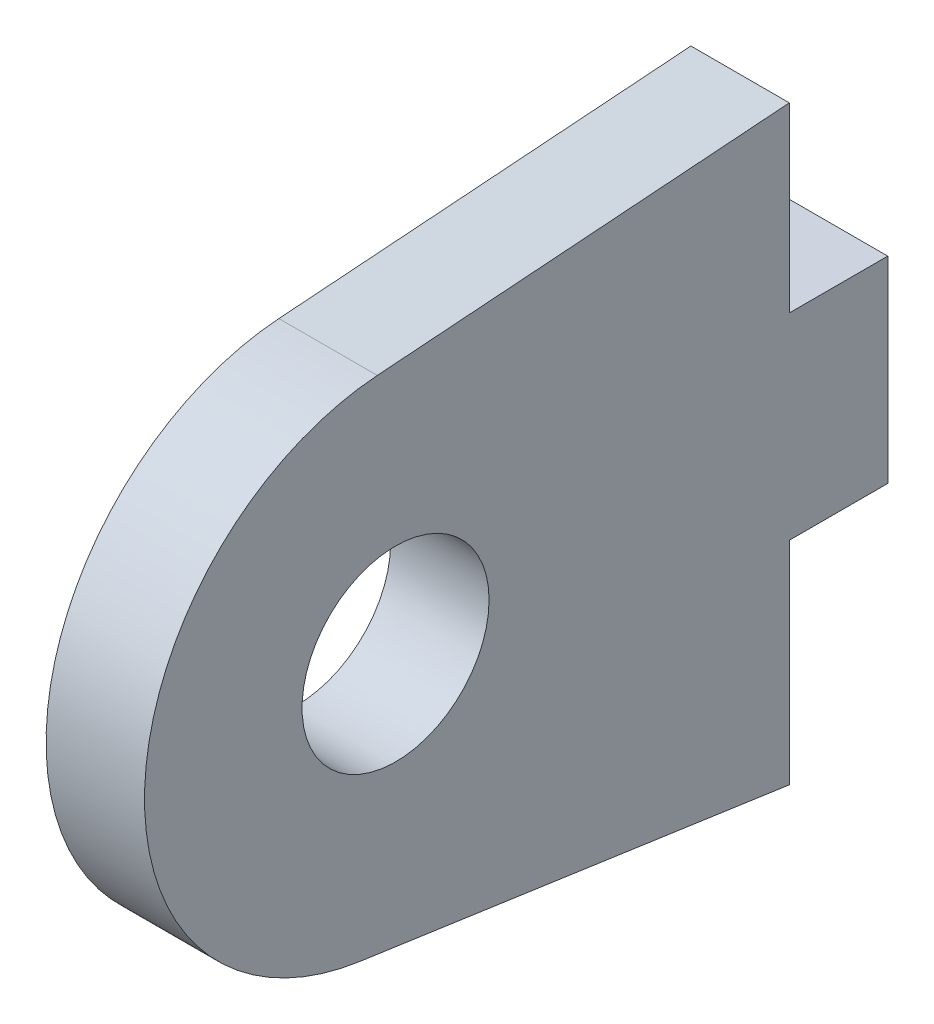
SolidWorks part; units mm, degrees
material "AISI 1020 Steel, Cold Rolled"
ref_plane "Front Plane" through (0, 0, 0) normal (1, 0, 0) x (0, 1, 0)
ref_plane "Top Plane" through (0, 0, 0) normal (0, 0, 1) x (0, 1, 0)
ref_plane "Right Plane" through (0, 0, 0) normal (0, 1, 0) x (-1, 0, 0)
sketch "Sketch1" plane through (0, 0, 0) normal (1, 0, 0) x (0, 1, 0)
  line L0 (-15.7577, 0) -> (-5, 0)
  line L1 (0, 0) -> (0, 20) construction
  line L2 (-15.7577, 0) -> (-12.6201, 21.8151)
  line L3 (14.2423, 0) -> (12.7162, 20.9273)
  line L4 (0, 0) -> (0, -5) construction
  line L5 (5, -5) -> (-5, -5)
  line L6 (-5, -5) -> (-5, 0)
  line L7 (5, -5) -> (5, 0)
  line L8 (5, 0) -> (14.2423, 0)
  line L9 (0, 0) -> (5, 0) construction
  line L10 (-5, 0) -> (0, 0) construction
  line L11 (0, 20) -> (0, 4.6155) construction
  circle A0 centre (0, 20) radius 4.75
  arc A1 (12.7162, 20.9273) -> (-12.6201, 21.8151) centre (0, 20) ccw
  arc A2 (0, 7.25) -> (12.7162, 20.9273) centre (0, 20) ccw construction
  circle A3 centre (0, 20) radius 12.75 construction
  point P4 (0, 0)
  point P11 (12, 20)
  point P17 (0, -5)
  dimension "D3" = 9.5
  dimension "D4" = 8
  dimension "D1" = 30
  dimension "D2" = 20
  dimension "D5" = 5
  dimension "D6" = 10
  dimension "D7" = 15.3845
extrude "Boss-Extrude1" add sketch "Sketch1" along normal mid plane 5
